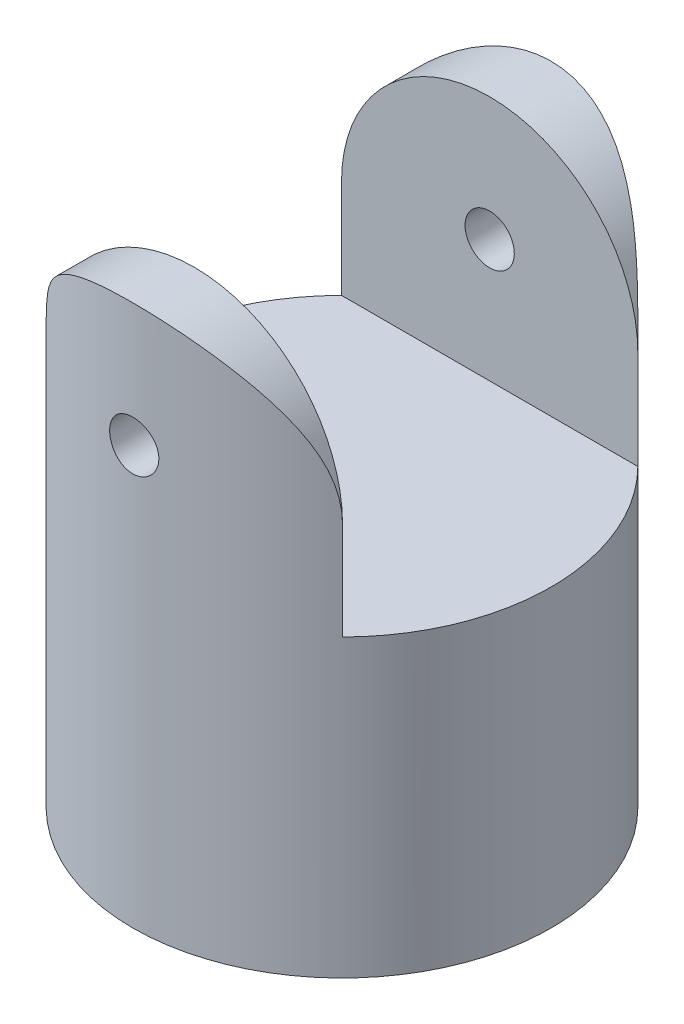
SolidWorks part; units mm, degrees
ref_plane "Alzado" through (0, 0, 0) normal (0, 0, 1) x (1, 0, 0)
ref_plane "Planta" through (0, 0, 0) normal (0, 1, 0) x (1, 0, 0)
ref_plane "Vista lateral" through (0, 0, 0) normal (1, 0, 0) x (0, 0, -1)
sketch "Croquis1" plane through (0, 0, 0) normal (0, 1, 0) x (1, 0, 0)
  circle A0 centre (0, 0) radius 4.25
  dimension "D1" = 8.5
extrude "Saliente-Extruir1" add sketch "Croquis1" along normal blind 11
sketch "Croquis2" plane through (0, 11, 0) normal (0, 1, 0) x (1, 0, 0)
  line L1 (4.25, 3) -> (-4.25, 3)
  line L2 (4.25, 3) -> (4.25, -3)
  line L3 (4.25, -3) -> (-4.25, -3)
  line L4 (-4.25, 3) -> (-4.25, -3)
  line L5 (4.25, 3) -> (-4.25, -3) construction
  line L6 (4.25, -3) -> (-4.25, 3) construction
  circle A0 centre (0, 0) radius 4.25 construction
  point P0 (0, 0)
  dimension "D1" = 6
extrude "Cortar-Extruir1" cut sketch "Croquis2" against normal blind 5
sketch "Croquis4" plane through (0, 0, 0) normal (0, 0, 1) x (1, 0, 0)
  line L1 (3.0104, 11) -> (-3.0104, 11) construction
  line L2 (-3.0104, 11) -> (-3.0104, 6) construction
  line L3 (3.0104, 6) -> (3.0104, 11) construction
  line L4 (-3.0104, 7.9896) -> (-3.0104, 11)
  line L5 (-3.0104, 11) -> (0, 11)
  line L6 (0, 11) -> (3.0104, 11)
  line L7 (3.0104, 11) -> (3.0104, 7.9896)
  arc A0 (-3.0104, 7.9896) -> (3.0104, 7.9896) centre (0, 7.9896) cw
extrude "Cortar-Extruir2" cut sketch "Croquis4" against normal mid plane 10 contours L4 A0 L5 | L6 A0 L7
sketch "Croquis5" plane through (0, 0, 0) normal (0, 0, 1) x (1, 0, 0)
  line L0 (-2.9686, 8.4896) -> (2.9686, 8.4896) construction
  circle A0 centre (0, 8.4896) radius 0.5
  arc A5 (3.0104, 7.9896) -> (-3.0104, 7.9896) centre (0, 7.9896) ccw construction
  point P6 (0, 8.4896)
  point P9 (0, 8.4896)
  dimension "D1" = 1
  dimension "D2" = 0.5
extrude "Cortar-Extruir3" cut sketch "Croquis5" against normal mid plane 10
